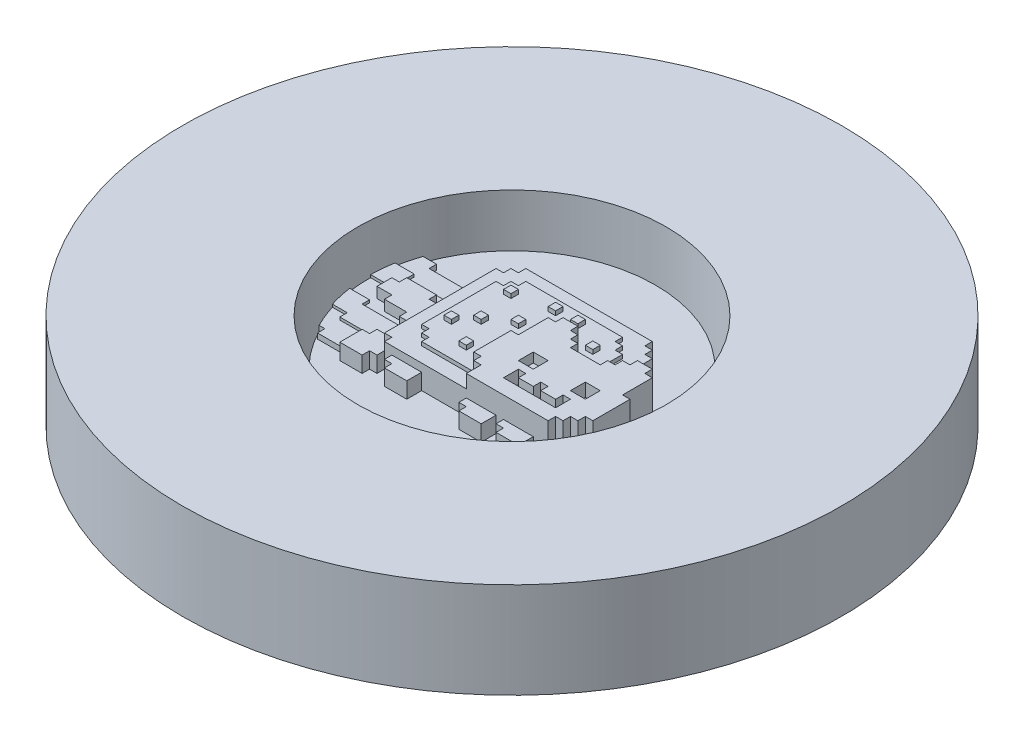
SolidWorks part; units mm, degrees
ref_plane "Front Plane" through (0, 0, 0) normal (0, 0, 1) x (1, 0, 0)
ref_plane "Top Plane" through (0, 0, 0) normal (0, 1, 0) x (1, 0, 0)
ref_plane "Right Plane" through (0, 0, 0) normal (1, 0, 0) x (0, 0, -1)
sketch "Sketch1" plane through (0, 0, 0) normal (0, 1, 0) x (1, 0, 0)
sketch "face" plane through (0, 0, 0) normal (0, 1, 0) x (1, 0, 0)
  line L0 (103.124, 88.9) -> (110.236, 88.9)
  line L1 (110.236, 88.9) -> (110.236, 85.344)
  line L2 (110.236, 85.344) -> (113.792, 85.344)
  line L3 (113.792, 85.344) -> (113.792, 81.788)
  line L4 (113.792, 81.788) -> (117.348, 81.788)
  line L5 (117.348, 81.788) -> (117.348, 78.232)
  line L6 (117.348, 78.232) -> (131.572, 78.232)
  line L7 (131.572, 78.232) -> (131.572, 81.788)
  line L8 (131.572, 81.788) -> (135.128, 81.788)
  line L9 (135.128, 81.788) -> (135.128, 85.344)
  line L10 (135.128, 85.344) -> (138.684, 85.344)
  line L11 (138.684, 85.344) -> (138.684, 88.9)
  line L12 (138.684, 88.9) -> (145.796, 88.9)
  line L13 (145.796, 88.9) -> (145.796, 85.344)
  line L14 (145.796, 85.344) -> (149.352, 85.344)
  line L15 (149.352, 85.344) -> (149.352, 71.12)
  line L16 (149.352, 71.12) -> (152.908, 71.12)
  line L17 (152.908, 71.12) -> (152.908, 53.34)
  line L18 (152.908, 53.34) -> (149.352, 53.34)
  line L19 (149.352, 53.34) -> (149.352, 49.784)
  line L20 (149.352, 49.784) -> (145.796, 49.784)
  line L21 (145.796, 49.784) -> (145.796, 46.228)
  line L22 (145.796, 46.228) -> (142.24, 46.228)
  line L23 (142.24, 46.228) -> (142.24, 42.672)
  line L24 (142.24, 42.672) -> (103.124, 42.672)
  line L25 (103.124, 42.672) -> (103.124, 49.784)
  line L26 (103.124, 49.784) -> (99.568, 49.784)
  line L27 (99.568, 49.784) -> (99.568, 53.34)
  line L28 (99.568, 53.34) -> (96.012, 53.34)
  line L29 (96.012, 53.34) -> (96.012, 71.12)
  line L30 (96.012, 71.12) -> (99.568, 71.12)
  line L31 (99.568, 71.12) -> (99.568, 85.344)
  line L32 (99.568, 85.344) -> (103.124, 85.344)
  line L33 (110.236, 67.564) -> (110.236, 60.452)
  line L34 (110.236, 60.452) -> (117.348, 60.452)
  line L35 (117.348, 60.452) -> (117.348, 67.564)
  line L36 (117.348, 67.564) -> (110.236, 67.564)
  line L37 (135.128, 67.564) -> (135.128, 60.452)
  line L38 (135.128, 60.452) -> (142.24, 60.452)
  line L39 (142.24, 60.452) -> (142.24, 67.564)
  line L40 (142.24, 67.564) -> (135.128, 67.564)
  line L41 (113.792, 56.896) -> (113.792, 49.784)
  line L42 (113.792, 49.784) -> (138.684, 49.784)
  line L43 (138.684, 49.784) -> (138.684, 56.896)
  line L44 (138.684, 56.896) -> (135.128, 56.896)
  line L45 (135.128, 56.896) -> (135.128, 53.34)
  line L46 (135.128, 53.34) -> (128.016, 53.34)
  line L47 (128.016, 53.34) -> (128.016, 56.896)
  line L48 (128.016, 56.896) -> (124.46, 56.896)
  line L49 (124.46, 56.896) -> (124.46, 53.34)
  line L50 (124.46, 53.34) -> (117.348, 53.34)
  line L51 (117.348, 53.34) -> (117.348, 56.896)
  line L52 (117.348, 56.896) -> (113.792, 56.896)
  line L53 (103.124, 88.9) -> (103.124, 85.344)
sketch "poptart" plane through (0, 0, 0) normal (0, 1, 0) x (1, 0, 0)
  line L1 (135.128, 99.568) -> (131.572, 99.568)
  line L2 (131.572, 99.568) -> (131.572, 103.124)
  line L3 (131.572, 103.124) -> (128.016, 103.124)
  line L4 (128.016, 103.124) -> (128.016, 106.68)
  line L5 (128.016, 106.68) -> (67.564, 106.68)
  line L6 (67.564, 106.68) -> (67.564, 103.124)
  line L7 (67.564, 103.124) -> (64.008, 103.124)
  line L8 (64.008, 103.124) -> (64.008, 99.568)
  line L9 (64.008, 99.568) -> (60.452, 99.568)
  line L10 (60.452, 99.568) -> (60.452, 46.228)
  line L11 (60.452, 46.228) -> (64.008, 46.228)
  line L12 (64.008, 46.228) -> (64.008, 42.672)
  line L13 (64.008, 42.672) -> (135.128, 42.672)
  line L14 (142.24, 42.672) -> (103.124, 42.672) construction
  line L15 (135.128, 42.672) -> (145.796, 53.34)
  line L16 (145.796, 53.34) -> (145.796, 71.12)
  line L17 (145.796, 71.12) -> (135.128, 85.344)
  line L18 (135.128, 85.344) -> (135.128, 99.568)
sketch "feet tail" plane through (0, 0, 0) normal (0, 1, 0) x (1, 0, 0)
  line L0 (60.452, 74.676) -> (53.34, 74.676)
  line L1 (60.452, 99.568) -> (60.452, 46.228) construction
  line L2 (53.34, 74.676) -> (53.34, 78.232)
  line L3 (53.34, 78.232) -> (39.116, 78.232)
  line L4 (39.116, 78.232) -> (39.116, 74.676)
  line L5 (39.116, 74.676) -> (35.56, 74.676)
  line L6 (35.56, 74.676) -> (35.56, 67.564)
  line L7 (35.56, 67.564) -> (42.672, 67.564)
  line L8 (42.672, 67.564) -> (42.672, 64.008)
  line L9 (42.672, 64.008) -> (53.34, 64.008)
  line L10 (53.34, 64.008) -> (53.34, 60.452)
  line L11 (53.34, 60.452) -> (60.452, 60.452)
  line L12 (60.452, 60.452) -> (60.452, 74.676)
  line L13 (60.452, 53.34) -> (56.896, 53.34)
  line L14 (56.896, 53.34) -> (56.896, 49.784)
  line L15 (56.896, 49.784) -> (53.34, 49.784)
  line L16 (53.34, 49.784) -> (53.34, 46.228)
  line L17 (53.34, 46.228) -> (49.784, 46.228)
  line L18 (49.784, 46.228) -> (49.784, 35.56)
  line L19 (49.784, 35.56) -> (60.452, 35.56)
  line L20 (60.452, 35.56) -> (60.452, 39.116)
  line L21 (60.452, 39.116) -> (64.008, 39.116)
  line L22 (64.008, 39.116) -> (64.008, 46.228)
  line L23 (67.564, 42.672) -> (67.564, 39.116)
  line L24 (64.008, 42.672) -> (135.128, 42.672) construction
  line L25 (67.564, 39.116) -> (71.12, 39.116)
  line L26 (71.12, 39.116) -> (71.12, 35.56)
  line L27 (71.12, 35.56) -> (81.788, 35.56)
  line L28 (81.788, 35.56) -> (81.788, 42.672)
  line L29 (81.788, 42.672) -> (67.564, 42.672)
  line L30 (64.008, 46.228) -> (60.452, 46.228)
  line L31 (60.452, 46.228) -> (60.452, 53.34)
  line L33 (103.124, 42.672) -> (103.124, 39.116)
  line L34 (103.124, 39.116) -> (106.68, 39.116)
  line L35 (106.68, 39.116) -> (106.68, 35.56)
  line L36 (106.68, 35.56) -> (117.348, 35.56)
  line L37 (117.348, 35.56) -> (117.348, 42.672)
  line L38 (142.24, 42.672) -> (103.124, 42.672) construction
  line L39 (117.348, 42.672) -> (103.124, 42.672)
  line L40 (120.904, 42.672) -> (120.904, 39.116)
  line L41 (120.904, 39.116) -> (124.46, 39.116)
  line L42 (124.46, 39.116) -> (124.46, 35.56)
  line L43 (124.46, 35.56) -> (135.128, 35.56)
  line L44 (135.128, 35.56) -> (135.128, 42.672)
  line L45 (135.128, 42.672) -> (120.904, 42.672)
sketch "sprinkles" plane through (0, 0, 0) normal (0, 1, 0) x (1, 0, 0)
  line L1 (71.12, 67.564) -> (74.676, 67.564)
  line L2 (71.12, 67.564) -> (71.12, 64.008)
  line L3 (71.12, 64.008) -> (74.676, 64.008)
  line L4 (74.676, 67.564) -> (74.676, 64.008)
  line L5 (78.232, 74.676) -> (81.788, 74.676)
  line L6 (78.232, 74.676) -> (78.232, 71.12)
  line L7 (78.232, 71.12) -> (81.788, 71.12)
  line L8 (81.788, 74.676) -> (81.788, 71.12)
  line L9 (88.9, 81.788) -> (92.456, 81.788)
  line L10 (88.9, 81.788) -> (88.9, 78.232)
  line L11 (88.9, 78.232) -> (92.456, 78.232)
  line L12 (92.456, 81.788) -> (92.456, 78.232)
  line L13 (74.676, 92.456) -> (78.232, 92.456)
  line L14 (74.676, 92.456) -> (74.676, 88.9)
  line L15 (74.676, 88.9) -> (78.232, 88.9)
  line L16 (78.232, 92.456) -> (78.232, 88.9)
  line L17 (92.456, 96.012) -> (96.012, 96.012)
  line L18 (92.456, 96.012) -> (92.456, 92.456)
  line L19 (92.456, 92.456) -> (96.012, 92.456)
  line L20 (96.012, 96.012) -> (96.012, 92.456)
  line L21 (103.124, 96.012) -> (106.68, 96.012)
  line L22 (103.124, 96.012) -> (103.124, 92.456)
  line L23 (103.124, 92.456) -> (106.68, 92.456)
  line L24 (106.68, 96.012) -> (106.68, 92.456)
  line L25 (117.348, 88.9) -> (120.904, 88.9)
  line L26 (117.348, 88.9) -> (117.348, 85.344)
  line L27 (117.348, 85.344) -> (120.904, 85.344)
  line L28 (120.904, 88.9) -> (120.904, 85.344)
  line L29 (85.344, 60.452) -> (88.9, 60.452)
  line L30 (85.344, 60.452) -> (85.344, 56.896)
  line L31 (85.344, 56.896) -> (88.9, 56.896)
  line L32 (88.9, 60.452) -> (88.9, 56.896)
sketch "engrave poptart" plane through (0, 0, 0) normal (0, 1, 0) x (1, 0, 0)
  line L0 (71.12, 53.34) -> (74.676, 53.34)
  line L1 (74.676, 53.34) -> (74.676, 49.784)
  line L2 (74.676, 49.784) -> (99.8163, 49.76)
  line L3 (71.12, 53.34) -> (71.12, 56.896)
  line L4 (71.12, 56.896) -> (67.564, 56.896)
  line L5 (67.564, 56.896) -> (67.564, 92.456)
  line L6 (67.564, 92.456) -> (71.12, 92.456)
  line L7 (71.12, 92.456) -> (71.12, 96.012)
  line L8 (71.12, 96.012) -> (74.676, 96.012)
  line L9 (74.676, 96.012) -> (74.676, 99.568)
  line L10 (74.676, 99.568) -> (120.904, 99.568)
  line L11 (120.904, 99.568) -> (120.904, 96.012)
  line L12 (120.904, 96.012) -> (124.46, 96.012)
  line L13 (124.46, 96.012) -> (124.46, 92.456)
  line L14 (124.46, 92.456) -> (128.016, 92.456)
  line L15 (128.016, 92.456) -> (128.016, 67.564)
  line L16 (128.016, 67.564) -> (128.016, 64.008)
  line L17 (128.016, 64.008) -> (99.568, 49.784)
  line L18 (99.568, 49.784) -> (99.8163, 49.76)
sketch "rainbow tail" plane through (0, 0, 0) normal (0, 1, 0) x (1, 0, 0)
  line L0 (0, 39.116) -> (0, 49.784)
  line L1 (0, 49.784) -> (7.112, 49.784)
  line L2 (7.112, 49.784) -> (7.112, 53.34)
  line L3 (7.112, 53.34) -> (35.56, 53.34)
  line L4 (35.56, 53.34) -> (35.56, 49.784)
  line L5 (35.56, 49.784) -> (53.34, 49.784)
  line L6 (0, 39.116) -> (7.112, 39.116)
  line L7 (7.112, 39.116) -> (7.112, 42.672)
  line L8 (7.112, 42.672) -> (35.56, 42.672)
  line L9 (35.56, 42.672) -> (35.56, 39.116)
  line L10 (35.56, 39.116) -> (49.784, 39.116)
  line L11 (49.784, 46.228) -> (49.784, 35.56) construction
  line L12 (53.34, 49.784) -> (53.34, 46.228)
  line L13 (53.34, 46.228) -> (49.784, 46.228)
  line L14 (53.34, 60.452) -> (35.56, 60.452)
  line L15 (35.56, 60.452) -> (35.56, 64.008)
  line L16 (35.56, 64.008) -> (7.112, 64.008)
  line L17 (7.112, 64.008) -> (7.112, 60.452)
  line L18 (7.112, 60.452) -> (0, 60.452)
  line L19 (0, 60.452) -> (0, 71.12)
  line L20 (49.784, 46.228) -> (49.784, 39.116)
  line L21 (0, 71.12) -> (7.112, 71.12)
  line L22 (7.112, 71.12) -> (7.112, 74.676)
  line L23 (7.112, 74.676) -> (53.34, 74.676)
  line L24 (53.34, 74.676) -> (53.34, 60.452)
  line L25 (0, 81.788) -> (7.112, 81.788)
  line L26 (7.112, 81.788) -> (7.112, 85.344)
  line L27 (7.112, 85.344) -> (35.56, 85.344)
  line L28 (35.56, 85.344) -> (35.56, 81.788)
  line L29 (35.56, 81.788) -> (60.452, 81.788)
  line L30 (60.452, 81.788) -> (60.452, 92.456)
  line L31 (60.452, 92.456) -> (35.56, 92.456)
  line L32 (35.56, 92.456) -> (35.56, 96.012)
  line L33 (35.56, 96.012) -> (7.112, 96.012)
  line L34 (7.112, 96.012) -> (7.112, 92.456)
  line L35 (7.112, 92.456) -> (0, 92.456)
  line L36 (0, 92.456) -> (0, 81.788)
  circle A0 centre (0, 0) radius 68.1246
extrude "face-" add sketch "face" along normal blind 17.78
extrude "feettail" add sketch "feet tail" along normal blind 7.62
extrude "poptart-" add sketch "poptart" along normal blind 11.43
extrude "sprinkle" add sketch "sprinkles" along normal blind 15.24
extrude "engrave" add sketch "engrave poptart" along normal blind 13.208
sketch "Sketch2" plane through (0, 0, 0) normal (0, 1, 0) x (1, 0, 0)
  circle A0 centre (93.98, 73.66) radius 68.58
sketch "Sketch4" plane through (0, 0, 0) normal (0, 1, 0) x (1, 0, 0)
  circle A0 centre (93.98, 73.66) radius 157.48
  circle A1 centre (93.98, 73.66) radius 81.28 construction
  circle A2 centre (93.98, 73.66) radius 73.66
  dimension "D1" = 76.2
extrude "CUPCAKE" add sketch "Sketch2" against normal blind 15.24
extrude "retaining" add sketch "Sketch4" against normal blind 45.72 from offset 21.59
sketch "Sketch5" plane through (0, 0, 0) normal (0, 1, 0) x (1, 0, 0)
  circle A1 centre (93.98, 73.66) radius 81.28
extrude "cupcake body" add sketch "Sketch5" against normal blind 6.35 from offset 17.78 offset against normal yes
sketch "Sketch10" plane through (0, 0, 0) normal (0, 1, 0) x (1, 0, 0)
  line L0 (60.452, 92.456) -> (35.56, 92.456)
  line L1 (35.56, 92.456) -> (35.56, 96.012)
  line L2 (35.56, 96.012) -> (29.1448, 96.012)
  line L4 (26.4026, 85.344) -> (35.56, 85.344)
  line L5 (35.56, 85.344) -> (35.56, 81.788)
  line L6 (35.56, 81.788) -> (60.452, 81.788)
  line L7 (60.452, 81.788) -> (60.452, 92.456)
  line L8 (35.56, 74.676) -> (25.4075, 74.676)
  line L14 (26.0826, 64.008) -> (35.56, 64.008)
  line L15 (35.56, 64.008) -> (35.56, 60.452)
  line L16 (35.56, 60.452) -> (53.34, 60.452)
  line L17 (53.34, 60.452) -> (53.34, 64.008)
  line L18 (53.34, 64.008) -> (42.672, 64.008)
  line L19 (42.672, 64.008) -> (42.672, 67.564)
  line L20 (42.672, 67.564) -> (35.56, 67.564)
  line L21 (35.56, 74.676) -> (35.56, 67.564) construction
  line L22 (35.56, 67.564) -> (42.672, 67.564) construction
  line L23 (35.56, 67.564) -> (35.56, 74.676)
  line L24 (53.34, 49.784) -> (35.56, 49.784)
  line L25 (35.56, 49.784) -> (35.56, 53.34)
  line L26 (35.56, 53.34) -> (28.4795, 53.34)
  line L28 (32.8003, 42.672) -> (35.56, 42.672)
  line L29 (35.56, 42.672) -> (35.56, 39.116)
  line L30 (35.56, 39.116) -> (49.784, 39.116)
  line L31 (49.784, 39.116) -> (49.784, 46.228)
  line L32 (49.784, 46.228) -> (53.34, 46.228)
  line L33 (53.34, 46.228) -> (53.34, 49.784)
  arc A0 (29.1448, 96.012) -> (26.4026, 85.344) centre (93.98, 73.66) ccw
  arc A1 (28.4795, 53.34) -> (32.8003, 42.672) centre (93.98, 73.66) ccw
  arc A2 (25.4075, 74.676) -> (26.0826, 64.008) centre (93.98, 73.66) ccw
extrude "Boss-Extrude1" add sketch "Sketch10" along normal blind 2.54
sketch "Sketch11" plane through (0, 0, 0) normal (0, 1, 0) x (1, 0, 0)
  line L0 (26.0826, 64.008) -> (35.56, 64.008)
  line L1 (35.56, 64.008) -> (35.56, 60.452)
  line L2 (35.56, 60.452) -> (60.452, 60.452)
  line L3 (35.56, 60.452) -> (60.452, 60.452) construction
  line L4 (60.452, 60.452) -> (60.452, 53.34)
  line L5 (60.452, 53.34) -> (56.896, 53.34)
  line L6 (56.896, 53.34) -> (56.896, 49.784)
  line L7 (56.896, 53.34) -> (56.896, 49.784) construction
  line L8 (56.896, 53.34) -> (56.896, 49.784) construction
  line L9 (56.896, 49.784) -> (35.56, 49.784)
  line L10 (35.56, 49.784) -> (35.56, 53.34)
  line L11 (35.56, 53.34) -> (28.4795, 53.34)
  line L12 (60.452, 81.788) -> (60.452, 74.676)
  line L13 (60.452, 74.676) -> (53.34, 74.676)
  line L14 (53.34, 74.676) -> (53.34, 78.232)
  line L15 (53.34, 74.676) -> (53.34, 78.232) construction
  line L16 (53.34, 78.232) -> (39.116, 78.232) construction
  line L17 (53.34, 78.232) -> (39.116, 78.232)
  line L18 (39.116, 78.232) -> (39.116, 74.676)
  line L19 (7.112, 74.676) -> (53.34, 74.676) construction
  line L20 (39.116, 78.232) -> (39.116, 74.676) construction
  line L21 (39.116, 74.676) -> (25.4075, 74.676)
  line L22 (26.4026, 85.344) -> (35.56, 85.344)
  line L24 (35.56, 85.344) -> (35.56, 81.788)
  line L25 (35.56, 81.788) -> (60.452, 81.788)
  arc A0 (26.4026, 85.344) -> (25.4075, 74.676) centre (93.98, 73.66) ccw
  arc A1 (26.0826, 64.008) -> (28.4795, 53.34) centre (93.98, 73.66) ccw
extrude "Boss-Extrude2" add sketch "Sketch11" along normal blind 3.81
